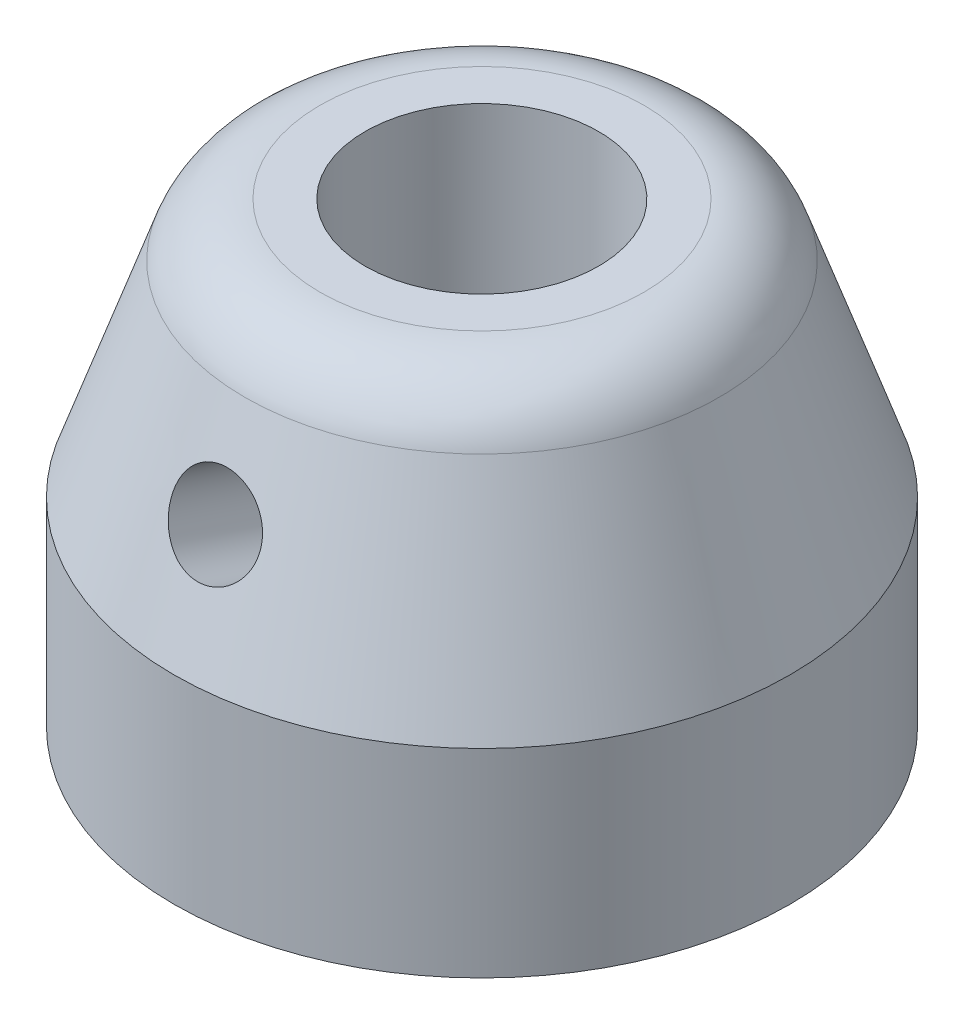
SolidWorks part; units mm, degrees
ref_plane "Ön Düzlem" through (0, 0, 0) normal (0, 0, 1) x (1, 0, 0)
ref_plane "Üst Düzlem" through (0, 0, 0) normal (0, 1, 0) x (1, 0, 0)
ref_plane "Sağ Düzlem" through (0, 0, 0) normal (1, 0, 0) x (0, 0, -1)
sketch "Çizim1" plane through (0, 0, 0) normal (0, 0, 1) x (1, 0, 0)
  line L0 (0, 46) -> (0, 0)
  line L1 (0, 0) -> (31, 0)
  line L2 (31, 0) -> (31, 20)
  line L3 (31, 20) -> (22, 46)
  line L4 (22, 46) -> (0, 46)
  dimension "D1" = 46
  dimension "D2" = 31
  dimension "D3" = 20
  dimension "D4" = 22
revolve "Döndür1" add sketch "Çizim1" angle 360 about L0
hole_wizard "M25x1.5 Dişli Delik1" positions "3B Çizim1" profile "Çizim3" tap size "M25x1.5" standard "DIN"
sketch3d "3B Çizim1"
  point P0 (0, 0, 0)
  point P3 (0.0009, 46, 0.0159)
sketch "Çizim3" plane through (0.0009, 46, 0.0159) normal (1, 0, 0) x (0, 0, 1)
  line L0 (0, 0) -> (0, 46)
  line L1 (0, 46) -> (11.75, 46)
  line L2 (11.75, 46) -> (11.75, 0)
  line L5 (11.75, 0) -> (0, 0)
  line L11 (0, -6.35) -> (0, 107.95) construction
  dimension "Thru Tap Drill Dia." = 23.5
  dimension "Thru Tap Drill Depth" = 46
cosmetic thread "Delik Dişi1" parameters "D2"=25
cosmetic thread "Delik Dişi2" parameters "D2"=25
fillet "Radyus1" radius 8 1 edges at (0, 46, 22)
sketch "Çizim4" plane through (0, 0, 0) normal (1, 0, 0) x (0, 0, -1)
  line L0 (-23.8634, 40.6169) -> (-31, 20) construction
  line L1 (-23.8634, 40.6169) -> (-31, 20) construction
ref_plane "Düzlem2" through (0, 11.7226, 33.8653) normal (0, 0.3271, 0.945) x (1, 0, 0)
hole_wizard "M10x1.0 Dişli Delik2" positions "Çizim12" profile "Çizim13" tap size "M10x1.0" standard "DIN"
sketch "Çizim12" plane through (0, 11.7226, 33.8653) normal (0, 0.3271, 0.945) x (1, 0, 0)
  line L0 (0, 30.5764) -> (0, 8.7593) construction
  point P0 (0, 20.5764)
  dimension "D1" = 10
sketch "Çizim13" plane through (0, 31.167, 27.1345) normal (1, 0, 0) x (0, -0.945, 0.3271)
  line L0 (0, 0) -> (0, 12.7039)
  line L1 (0, 12.7039) -> (4.5, 10)
  line L2 (4.5, 10) -> (4.5, 0)
  line L5 (4.5, 0) -> (0, 0)
  line L10 (0, 12.7039) -> (-4.5, 10) construction
  line L11 (0, -6.35) -> (0, 107.95) construction
  dimension "Tap Drill Dia." = 9
  dimension "Tap Drill Depth" = 10
  dimension "Drill Angle" = 118
cosmetic thread "Delik Dişi4" parameters "D1"=10, "D2"=10
sketch "Çizim14" plane through (0, 0, 0) normal (1, 0, 0) x (0, 0, -1)
  line L0 (0, 0) -> (-18.2034, 0)
  line L1 (-31, 0) -> (31, 0) construction
  line L2 (0, 0) -> (0, 2)
  line L3 (0, 2) -> (-12.5, 2)
  arc A0 (-12.5, 2) -> (-18.2034, 0) centre (0, -42.778) ccw
  point P7 (0, 0)
  dimension "D3" = 46.49
  dimension "D1" = 2
  dimension "D2" = 12.5
revolve "Kes-Döndür1" cut sketch "Çizim14" angle 360 about L2
